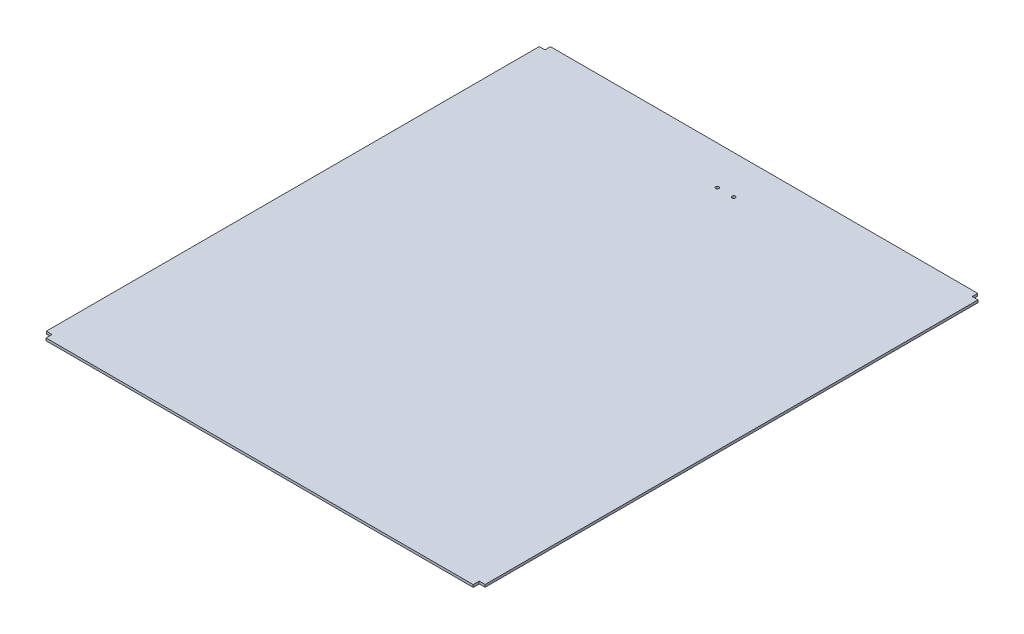
SolidWorks part; units mm, degrees
ref_plane "Front Plane" through (0, 0, 0) normal (0, 0, 1) x (1, 0, 0)
ref_plane "Top Plane" through (0, 0, 0) normal (0, 1, 0) x (1, 0, 0)
ref_plane "Right Plane" through (0, 0, 0) normal (1, 0, 0) x (0, 0, -1)
sketch "Sketch1" plane through (0, 0, 0) normal (0, 1, 0) x (1, 0, 0)
  line L1 (0.0465, 0.2911) -> (534.0465, 0.2911)
  line L2 (0.0465, 0.2911) -> (0.0465, 600.2911)
  line L3 (0.0465, 600.2911) -> (534.0465, 600.2911)
  line L4 (534.0465, 0.2911) -> (534.0465, 600.2911)
extrude "Boss-Extrude1" add sketch "Sketch1" along normal blind 3
ref_plane "Plane1" through (534.0465, 3, -600.2911) normal (0, 0, -1) x (-1, 0, 0)
sketch "Sketch3" plane through (0, 0, 0) normal (0, 1, 0) x (1, 0, 0)
  line L1 (7, 607) -> (527, 607)
  line L2 (7, 607) -> (7, -7)
  line L3 (7, -7) -> (527, -7)
  line L4 (527, 607) -> (527, -7)
extrude "Boss-Extrude2" add sketch "Sketch3" along normal blind 3
sketch "Sketch4" plane through (0, 3, 0) normal (0, 1, 0) x (1, 0, 0)
  circle A0 centre (257.025, 560) radius 2
  circle A1 centre (277.025, 560) radius 2
  point P4 (0, 0)
extrude "Cut-Extrude2" cut sketch "Sketch4" against normal blind 10
